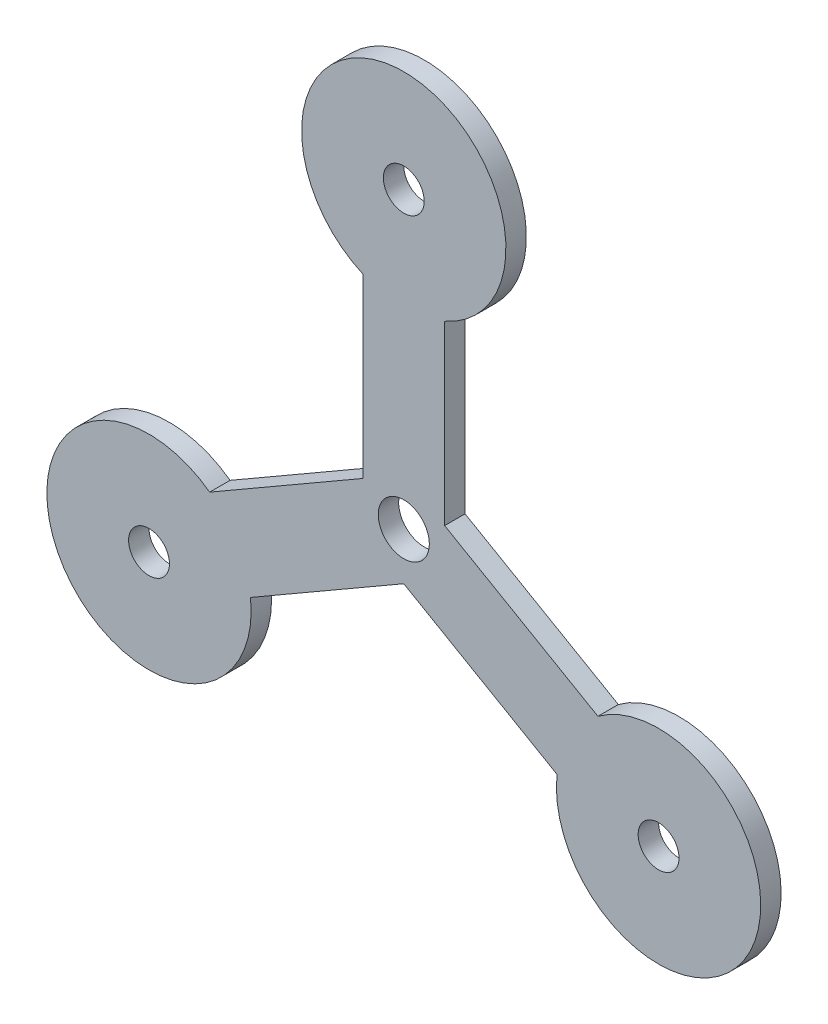
SolidWorks part; units mm, degrees
ref_plane "Front Plane" through (0, 0, 0) normal (0, 0, 1) x (1, 0, 0)
ref_plane "Top Plane" through (0, 0, 0) normal (0, 1, 0) x (1, 0, 0)
ref_plane "Right Plane" through (0, 0, 0) normal (1, 0, 0) x (0, 0, -1)
sketch "Sketch1" plane through (0, 0, 0) normal (0, 0, 1) x (1, 0, 0)
  line L0 (0, 0) -> (0, 144) construction
  line L1 (20, 144) -> (-20, 144)
  line L6 (0, 0) -> (124.7077, -72) construction
  line L7 (0, 0) -> (-124.7077, -72) construction
  line L8 (114.7077, -89.3205) -> (134.7077, -54.6795)
  line L9 (-114.7077, -89.3205) -> (-134.7077, -54.6795)
  line L10 (-134.7077, -54.6795) -> (-20, 11.547)
  line L11 (-20, 11.547) -> (-20, 144)
  line L12 (20, 144) -> (20, 11.547)
  line L13 (20, 11.547) -> (134.7077, -54.6795)
  line L14 (114.7077, -89.3205) -> (0, -23.094)
  line L15 (0, -23.094) -> (-114.7077, -89.3205)
  point P6 (0, 144)
  point P10 (0, 0)
  point P12 (124.7077, -72)
  point P15 (-124.7077, -72)
  dimension "D1" = 3
extrude "Boss-Extrude2" add sketch "Sketch1" along normal blind 10
sketch "Sketch3" plane through (0, 0, 10) normal (0, 0, 1) x (1, 0, 0)
  line L0 (-134.7077, -54.6795) -> (-114.7077, -89.3205) construction
  circle A0 centre (-124.7077, -72) radius 50
  circle A1 centre (0, 144) radius 50
  circle A2 centre (124.7077, -72) radius 50
  point P11 (0, 0)
  dimension "D1" = 3
extrude "Boss-Extrude3" add sketch "Sketch3" against normal blind 10
sketch "Sketch4" plane through (0, 0, 10) normal (0, 0, 1) x (1, 0, 0)
  circle A1 centre (0, 144) radius 10
  circle A2 centre (124.7077, -72) radius 10
  circle A3 centre (-124.7077, -72) radius 10
  point P9 (0, 0)
  dimension "D1" = 3
extrude "Boss-Extrude4" add sketch "Sketch4" along normal blind 90
sketch "Sketch5" plane through (0, 0, 100) normal (0, 0, 1) x (1, 0, 0)
  circle A0 centre (0, 144) radius 10
extrude "Cut-Extrude1" cut sketch "Sketch5" against normal blind 30
sketch "Sketch6" plane through (0, 0, 10) normal (0, 0, 1) x (1, 0, 0)
  circle A0 centre (0, 0) radius 13
extrude "Cut-Extrude2" cut sketch "Sketch6" against normal blind 10
sketch "Sketch7" plane through (0, 0, 70) normal (0, 0, 1) x (1, 0, 0)
  circle A0 centre (0, 144) radius 10
extrude "Boss-Extrude5" add sketch "Sketch7" along normal blind 30
sketch "Sketch8" plane through (0, 0, 10) normal (0, 0, 1) x (1, 0, 0)
  circle A0 centre (0, 0) radius 20.3692
extrude "Boss-Extrude6" add sketch "Sketch8" against normal blind 10
sketch "Sketch9" plane through (0, 0, 100) normal (0, 0, 1) x (1, 0, 0)
  circle A0 centre (-124.7077, -72) radius 10
  circle A1 centre (0, 144) radius 10
  circle A2 centre (124.7077, -72) radius 10
  point P10 (0, 0)
  dimension "D1" = 3
extrude "Cut-Extrude3" cut sketch "Sketch9" against normal blind 100
sketch "Sketch10" plane through (0, 0, 10) normal (0, 0, 1) x (1, 0, 0)
  circle A0 centre (0, 0) radius 10
extrude "Cut-Extrude4" cut sketch "Sketch10" against normal blind 10
sketch "Sketch11" plane through (0, 0, 10) normal (0, 0, 1) x (1, 0, 0)
  circle A0 centre (0, 0) radius 12.5
extrude "Cut-Extrude5" cut sketch "Sketch11" against normal blind 10
scale "Scale1" scale about centroid uniform scaling yes scale factor 0.2
